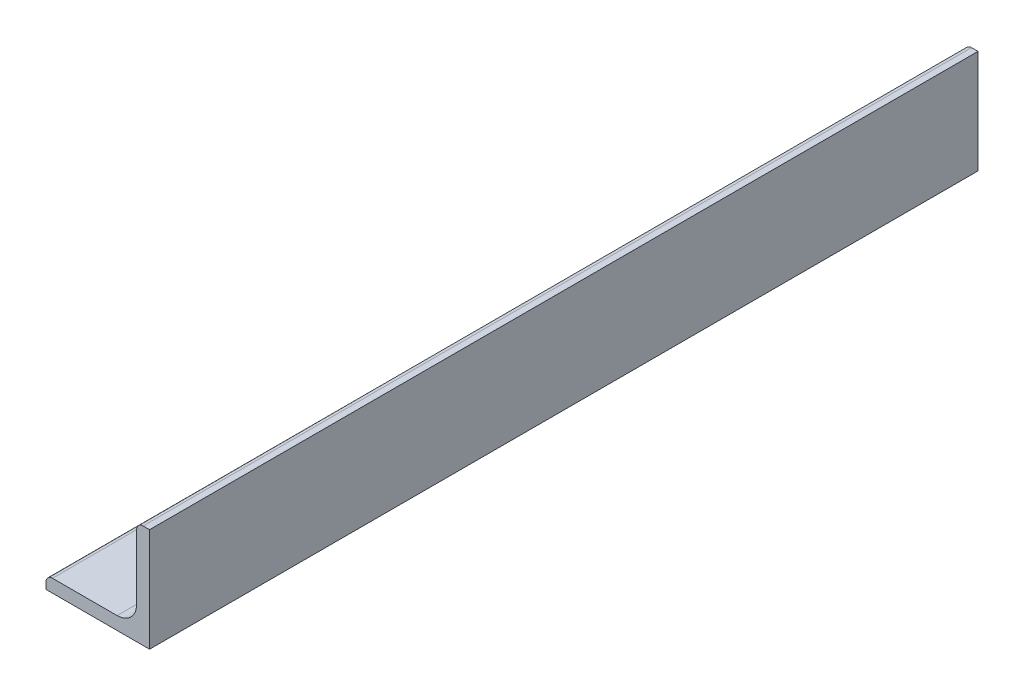
SolidWorks part; units mm, degrees
ref_plane "Front Plane" through (0, 0, 0) normal (0, 0, 1) x (1, 0, 0)
ref_plane "Top Plane" through (0, 0, 0) normal (0, 1, 0) x (1, 0, 0)
ref_plane "Right Plane" through (0, 0, 0) normal (1, 0, 0) x (0, 0, -1)
sketch "Sketch0" plane through (0, 0, 0) normal (0, 0, 1) x (1, 0, 0)
  line L0 (-12.7, -12.7) -> (12.7, -12.7)
  line L1 (12.7, -12.7) -> (12.7, 12.7)
  line L2 (12.7, 0) -> (0, 0) construction
  line L3 (0, 0) -> (0, -12.7) construction
  line L4 (9.525, -4.7498) -> (9.525, 12.7) construction
  line L5 (4.7498, -9.525) -> (-12.7, -9.525) construction
  arc A0 (9.525, -4.7498) -> (4.7498, -9.525) centre (4.7498, -4.7498) cw
  point P3 (8.1264, -8.1264)
  dimension "Inside Corner Radius" = 4.7752
  dimension "Outside Height" = 25.4
  dimension "Inside Height" = 22.225
  dimension "Inside Width" = 22.225
  dimension "Wall Thickness" = 3.175
  dimension "D1" = 3.175
  dimension "Outside Width" = 25.4
sketch "Sketch1" plane through (0, 0, 0) normal (1, 0, 0) x (0, 0, -1)
  line L0 (101.6, 0) -> (-101.6, 0)
  point P4 (0, 0)
  dimension "Length" = 203.2
sketch "Sketch2" plane through (0, 0, 0) normal (0, 0, 1) x (1, 0, 0)
  line L0 (-12.7, -12.7) -> (12.7, -12.7)
  line L1 (12.7, -12.7) -> (12.7, 12.7)
  line L2 (12.7, 12.7) -> (9.525, 12.7) construction
  line L3 (9.525, 11.1125) -> (9.525, -4.7498)
  line L4 (4.7498, -9.525) -> (-11.1125, -9.525)
  line L5 (-12.7, -12.7) -> (-12.7, -9.525) construction
  line L6 (11.1125, 12.7) -> (12.7, 12.7)
  line L7 (-12.7, -11.1125) -> (-12.7, -12.7)
  line L8 (12.7, 0) -> (0, 0) construction
  line L9 (0, 0) -> (0, -12.7) construction
  arc A0 (9.525, 11.1125) -> (11.1125, 12.7) centre (11.1125, 11.1125) cw
  arc A1 (-12.7, -11.1125) -> (-11.1125, -9.525) centre (-11.1125, -11.1125) cw
  arc A2 (9.525, -4.7498) -> (4.7498, -9.525) centre (4.7498, -4.7498) cw
  dimension "Inside Radius" = 4.7752
  dimension "Height" = 25.4
  dimension "Width" = 25.4
  dimension "Thickness" = 3.175
extrude "Boss-Extrude1" add sketch "Sketch2" along normal mid plane 203.2
sketch "Break Locations" plane through (0, 0, 0) normal (1, 0, 0) x (0, 0, -1)
  line L0 (-75.692, 0) -> (75.692, 0)
  line L1 (-101.6, -12.7) -> (-101.6, 12.7) construction
  line L2 (101.6, -12.7) -> (101.6, 12.7) construction
  point P0 (-80.01, 0)
  point P1 (80.01, 0)
  point P10 (0, 0)
  point P11 (75.692, 0)
  point P13 (-75.692, 0)
  dimension "D1" = 21.59
  dimension "D2" = 21.59
  dimension "D3" = 25.908
equation "\"D1@Break Locations\" = .85 * \"Height@Sketch2\""
equation "\"D2@Break Locations\"=\"D1@Break Locations\""
equation "\"Thickness@Sketch2\"=\"wall thickness@sketch0\""
equation "\"Height@Sketch2\"=\"outside height@sketch0\""
equation "\"Width@Sketch2\"=\"outside width@sketch0\""
equation "\"Inside Radius@Sketch2\"=\"inside corner radius@sketch0\""
equation "\"Length@Boss-Extrude1\"=\"length@sketch1\""
equation "\"D3@Break Locations\"=\"D2@Break Locations\"*1.2"
equation "\"D1@Sketch0\"=\"Wall Thickness@Sketch0\""
